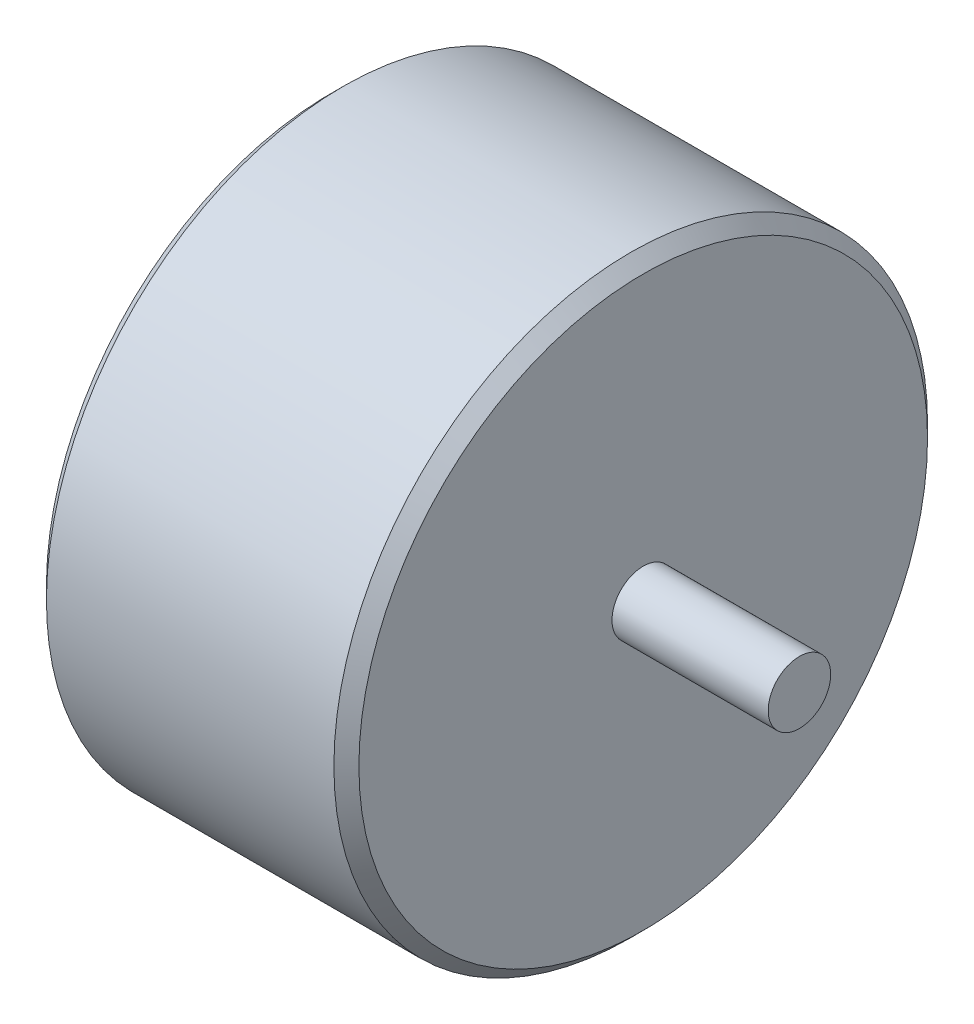
SolidWorks part; units mm, degrees
material "Plain Carbon Steel"
ref_plane "Front Plane" through (0, 0, 0) normal (0, 0, 1) x (1, 0, 0)
ref_plane "Top Plane" through (0, 0, 0) normal (0, 1, 0) x (1, 0, 0)
ref_plane "Right Plane" through (0, 0, 0) normal (1, 0, 0) x (0, 0, -1)
sketch "Sketch1" plane through (0, 0, 0) normal (1, 0, 0) x (0, 0, -1)
  circle A0 centre (0, 0) radius 12.065
  dimension "D1" = 24.13
extrude "Boss-Extrude1" add sketch "Sketch1" along normal blind 12.7
sketch "Sketch2" plane through (12.7, 0, 0) normal (1, 0, 0) x (0, 0, -1)
  circle A0 centre (0, 0) radius 1.27
  dimension "D1" = 2.54
extrude "Boss-Extrude2" add sketch "Sketch2" along normal blind 6.35
sketch "Sketch3" plane through (19.05, 0, 0) normal (1, 0, 0) x (0, 0, -1)
  line L0 (0, 2.54) -> (2.0304, 3.9542)
  line L1 (2.0304, 3.9542) -> (2.0304, 1.5261)
  line L2 (2.0304, 1.5261) -> (4.3789, 0.7639)
  line L3 (4.3789, 0.7639) -> (2.4774, -0.5605)
  line L4 (2.4774, -0.5605) -> (3.7496, -2.3871)
  line L5 (3.7496, -2.3871) -> (1.3439, -2.1553)
  line L6 (1.3439, -2.1553) -> (1.1376, -4.297)
  line L7 (1.1376, -4.297) -> (-0.6573, -2.4535)
  line L8 (-0.6573, -2.4535) -> (-2.8924, -3.3752)
  line L9 (-2.8924, -3.3752) -> (-2.3408, -0.9861)
  line L10 (-2.3408, -0.9861) -> (-4.4109, 0.5492)
  line L11 (-4.4109, 0.5492) -> (-2.1957, 1.2769)
  line L12 (-2.1957, 1.2769) -> (-1.9331, 4.0027)
  line L13 (-1.9331, 4.0027) -> (0, 2.54)
  circle A0 centre (0, 0) radius 2.54 construction
  circle A1 centre (0, 0) radius 4.445 construction
  dimension "D1" = 5.08
  dimension "D2" = 8.89
sketch "Sketch4" plane through (0, 0, 0) normal (-1, 0, 0) x (0, 0, 1)
  line L1 (-8.6713, 4.159) -> (-13.7134, 4.159)
  line L2 (-8.6713, 4.159) -> (-8.6713, -3.613)
  line L3 (-8.6713, -3.613) -> (-13.7134, -3.613)
  line L4 (-13.7134, 4.159) -> (-13.7134, -3.613)
extrude "Cut-Extrude1" cut sketch "Sketch4" against normal blind 3.81
chamfer "Chamfer1" distance 0.508 angle 45 2 edges at (0, -0.2884, 12.0616) (12.7, 0, -12.065)
